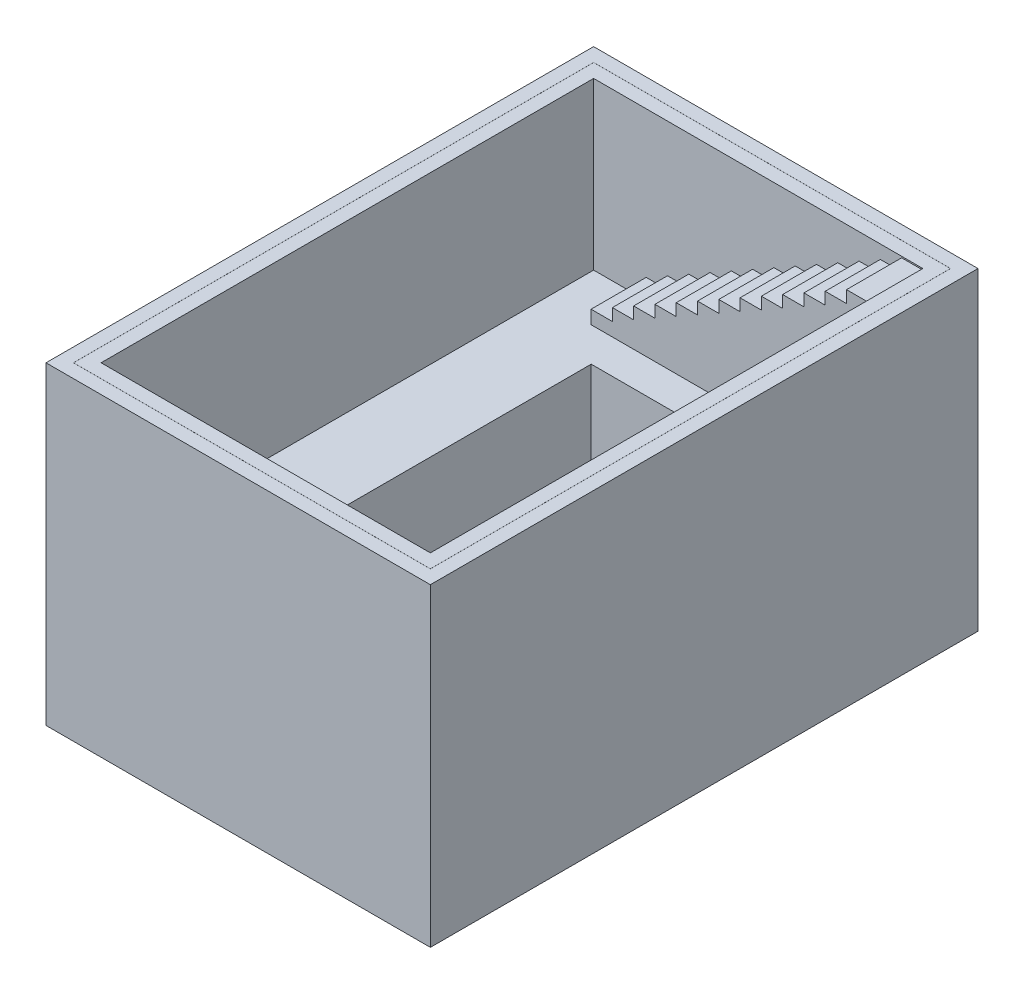
SolidWorks part; units mm, degrees
ref_plane "Alzado" through (0, 0, 0) normal (0, 0, 1) x (1, 0, 0)
ref_plane "Planta" through (0, 0, 0) normal (0, 1, 0) x (1, 0, 0)
ref_plane "Vista lateral" through (0, 0, 0) normal (1, 0, 0) x (0, 0, -1)
sketch "Croquis1" plane through (0, 0, 0) normal (0, 1, 0) x (1, 0, 0)
  line L0 (-2590, 3775) -> (-2590, -3775)
  line L1 (-2390, 3575) -> (2390, 3575)
  line L2 (-2390, 3575) -> (-2390, -3575)
  line L3 (-2390, -3575) -> (2390, -3575)
  line L4 (2390, 3575) -> (2390, -3575)
  line L5 (-2390, 3575) -> (2390, -3575) construction
  line L6 (-2390, -3575) -> (2390, 3575) construction
  line L7 (-2590, -3775) -> (2590, -3775)
  line L8 (2590, 3775) -> (2590, -3775)
  line L9 (-2590, 3775) -> (2590, 3775)
  point P0 (0, 0)
  point P6 (2390, -2022.9853)
  dimension "D1" = 4780
  dimension "D2" = 7150
  dimension "D3" = 200
extrude "Saliente-Extruir1" add sketch "Croquis1" along normal blind 4560
sketch "Croquis2" plane through (0, 0, -3575) normal (0, 0, 1) x (1, 0, 0)
  line L0 (2390, 4540) -> (2081, 4540)
  line L1 (2390, 4560) -> (2390, 0) construction
  line L2 (2081, 4540) -> (2081, 4365)
  line L3 (2081, 4365) -> (1772, 4365)
  line L4 (1772, 4365) -> (1772, 4190)
  line L5 (1772, 4190) -> (1463, 4190)
  line L6 (1463, 4190) -> (1463, 4015)
  line L7 (1463, 4015) -> (1154, 4015)
  line L8 (1154, 4015) -> (1154, 3840)
  line L9 (1154, 3840) -> (845, 3840)
  line L10 (845, 3840) -> (845, 3665)
  line L11 (845, 3665) -> (536, 3665)
  line L12 (536, 3665) -> (536, 3490)
  line L13 (536, 3490) -> (227, 3490)
  line L14 (227, 3490) -> (227, 3315)
  line L15 (227, 3315) -> (-82, 3315)
  line L16 (-82, 3315) -> (-82, 3140)
  line L17 (-82, 3140) -> (-391, 3140)
  line L18 (-391, 3140) -> (-391, 2965)
  line L19 (-391, 2965) -> (-700, 2965)
  line L20 (-700, 2965) -> (-700, 2790)
  line L21 (-700, 2790) -> (-1009, 2790)
  line L22 (-1009, 2790) -> (-1009, 2615)
  line L23 (-1009, 2615) -> (-1318, 2615)
  line L24 (-1318, 2615) -> (-1318, 2440)
  line L25 (-1318, 2440) -> (-1627, 2440)
  line L26 (-1627, 2440) -> (-1627, 2245)
  line L27 (-1627, 2245) -> (2390, 2245)
  line L28 (2390, 2245) -> (2390, 4540)
  dimension "D1" = 20
  dimension "D2" = 309
  dimension "D3" = 175
  dimension "D4" = 309
  dimension "D5" = 309
  dimension "D6" = 309
  dimension "D7" = 309
  dimension "D8" = 309
  dimension "D9" = 309
  dimension "D10" = 175
  dimension "D11" = 175
  dimension "D12" = 175
  dimension "D13" = 175
  dimension "D14" = 175
  dimension "D15" = 175
  dimension "D16" = 309
  dimension "D17" = 309
  dimension "D18" = 309
  dimension "D19" = 309
  dimension "D20" = 309
  dimension "D21" = 175
  dimension "D22" = 175
  dimension "D23" = 175
  dimension "D24" = 175
  dimension "D25" = 309
  dimension "D26" = 175
  dimension "D27" = 195
extrude "Saliente-Extruir2" add sketch "Croquis2" along normal blind 800
sketch "Croquis3" plane through (0, 0, 0) normal (0, 1, 0) x (1, 0, 0)
  line L1 (-1225, 2375) -> (1225, 2375)
  line L2 (-1225, 2375) -> (-1225, -2375)
  line L3 (-1225, -2375) -> (1225, -2375)
  line L4 (1225, 2375) -> (1225, -2375)
  line L5 (-1225, 2375) -> (1225, -2375) construction
  line L6 (-1225, -2375) -> (1225, 2375) construction
  line L7 (-2390, 3575) -> (2390, 3575)
  line L8 (-2390, 3575) -> (-2390, -3575)
  line L9 (-2390, -3575) -> (2390, -3575)
  line L10 (2390, 3575) -> (2390, -3575)
  line L11 (-2390, 3575) -> (2390, -3575) construction
  line L12 (-2390, -3575) -> (2390, 3575) construction
  point P0 (0, 0)
  point P6 (0, 0)
  dimension "D1" = 2450
  dimension "D2" = 4750
extrude "Saliente-Extruir3" add sketch "Croquis3" along normal blind 2150
sketch "Croquis4" plane through (0, 4560, 0) normal (0, 1, 0) x (1, 0, 0)
  line L0 (2591, -3776) -> (-2591, -3776)
  line L1 (2790, -3975) -> (-2790, -3975)
  line L2 (2790, -3975) -> (2790, 3975)
  line L3 (2790, 3975) -> (-2790, 3975)
  line L4 (-2790, -3975) -> (-2790, 3975)
  line L5 (2790, -3975) -> (-2790, 3975) construction
  line L6 (2790, 3975) -> (-2790, -3975) construction
  line L7 (-2591, -3776) -> (-2591, 3776)
  line L8 (2591, 3776) -> (-2591, 3776)
  line L9 (2591, -3776) -> (2591, 3776)
  point P0 (0, 0)
  dimension "D1" = 5580
  dimension "D2" = 7950
  dimension "D3" = 199
extrude "Saliente-Extruir4" add sketch "Croquis4" against normal up to surface (4560 mm away) separate body up to face at (0, 0, 0)
